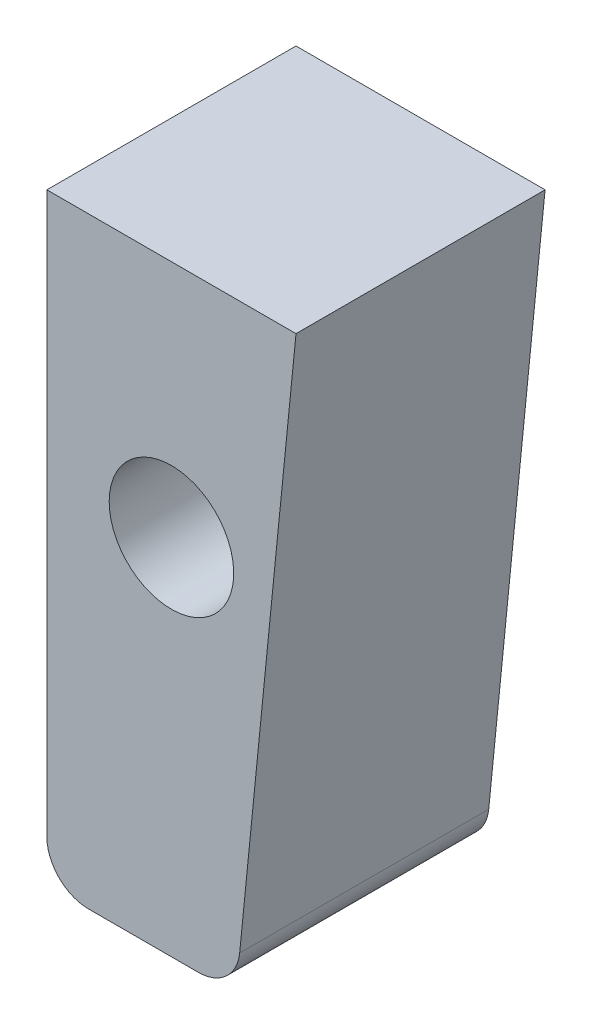
SolidWorks part; units mm, degrees
ref_plane "Front Plane" through (0, 0, 0) normal (0, 0, 1) x (1, 0, 0)
ref_plane "Top Plane" through (0, 0, 0) normal (0, 1, 0) x (1, 0, 0)
ref_plane "Right Plane" through (0, 0, 0) normal (1, 0, 0) x (0, 0, -1)
sketch "Sketch1" plane through (0, 0, 0) normal (0, 1, 0) x (1, 0, 0)
  line L1 (0, 0) -> (304.8, 0)
  line L2 (0, 0) -> (0, 304.8)
  line L3 (0, 304.8) -> (304.8, 304.8)
  line L4 (304.8, 0) -> (304.8, 304.8)
  dimension "D1" = 304.8
  dimension "D2" = 304.8
extrude "Boss-Extrude1" add sketch "Sketch1" along normal blind 736.6
sketch "Sketch2" plane through (0, 0, -304.8) normal (0, 0, -1) x (-1, 0, 0)
  line L0 (-304.8, 736.6) -> (0, 736.6) construction
  line L2 (0, 736.6) -> (0, 0) construction
  line L3 (-304.8, 736.6) -> (-231.2796, 0)
  line L4 (-304.8, 0) -> (0, 0) construction
  line L5 (-231.2796, 0) -> (-304.8, 0)
  line L6 (-304.8, 736.6) -> (-304.8, 0) construction
  line L7 (-304.8, 0) -> (-304.8, 736.6)
  circle A0 centre (-152.4, 444.5) radius 76.2
  dimension "D1" = 292.1
  dimension "D2" = 152.4
extrude "Cut-Extrude1" cut sketch "Sketch2" against normal up to next
fillet "Fillet1" radius 50.8 2 edges at (0, 0, -152.4) (231.2796, 0, -152.4)
